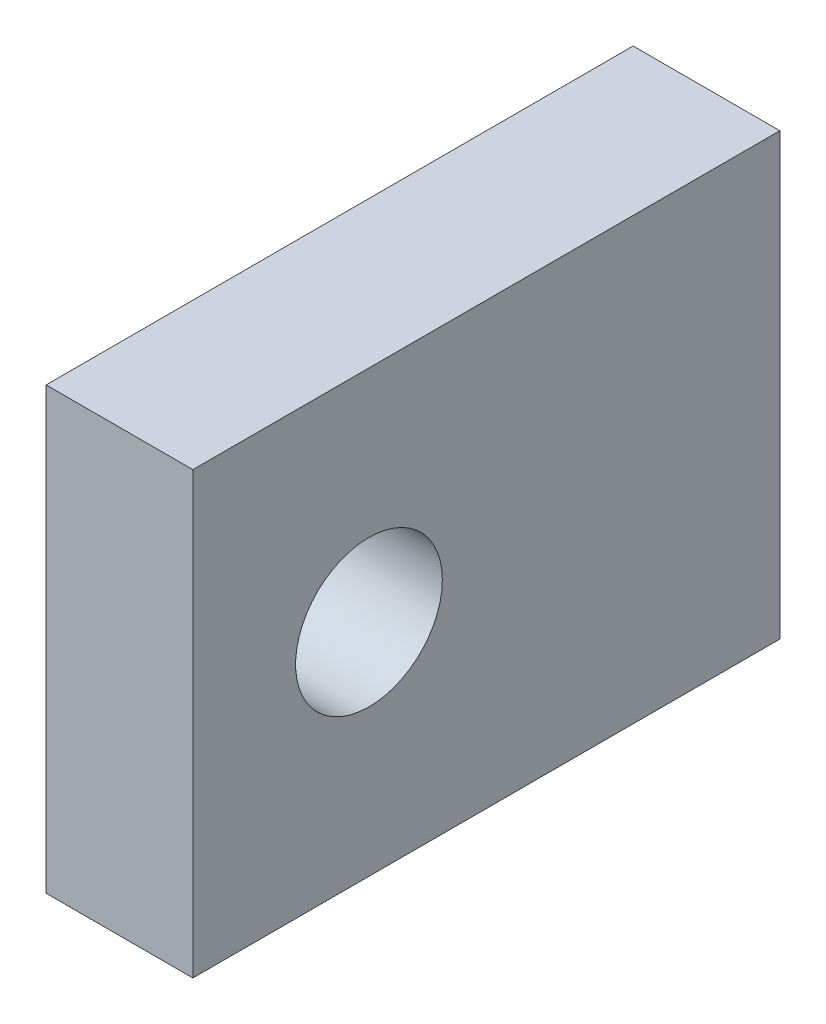
SolidWorks part; units mm, degrees
material "AISI 1020"
ref_plane "Front Plane" through (0, 0, 0) normal (0, 0, 1) x (1, 0, 0)
ref_plane "Top Plane" through (0, 0, 0) normal (0, 1, 0) x (1, 0, 0)
ref_plane "Right Plane" through (0, 0, 0) normal (1, 0, 0) x (0, 0, -1)
sketch "Sketch1" plane through (0, 0, 0) normal (1, 0, 0) x (0, 0, -1)
  line L1 (-25.4, -19.05) -> (25.4, -19.05)
  line L2 (-25.4, -19.05) -> (-25.4, 19.05)
  line L3 (-25.4, 19.05) -> (25.4, 19.05)
  line L4 (25.4, -19.05) -> (25.4, 19.05)
  line L5 (-25.4, -19.05) -> (25.4, 19.05) construction
  line L6 (-25.4, 19.05) -> (25.4, -19.05) construction
  circle A0 centre (-10.16, 0) radius 6.35
  point P0 (0, 0)
  dimension "D3" = 12.7
  dimension "D4" = 15.24
  dimension "D1" = 50.8
  dimension "D2" = 38.1
extrude "Boss-Extrude1" add sketch "Sketch1" along normal blind 12.7
